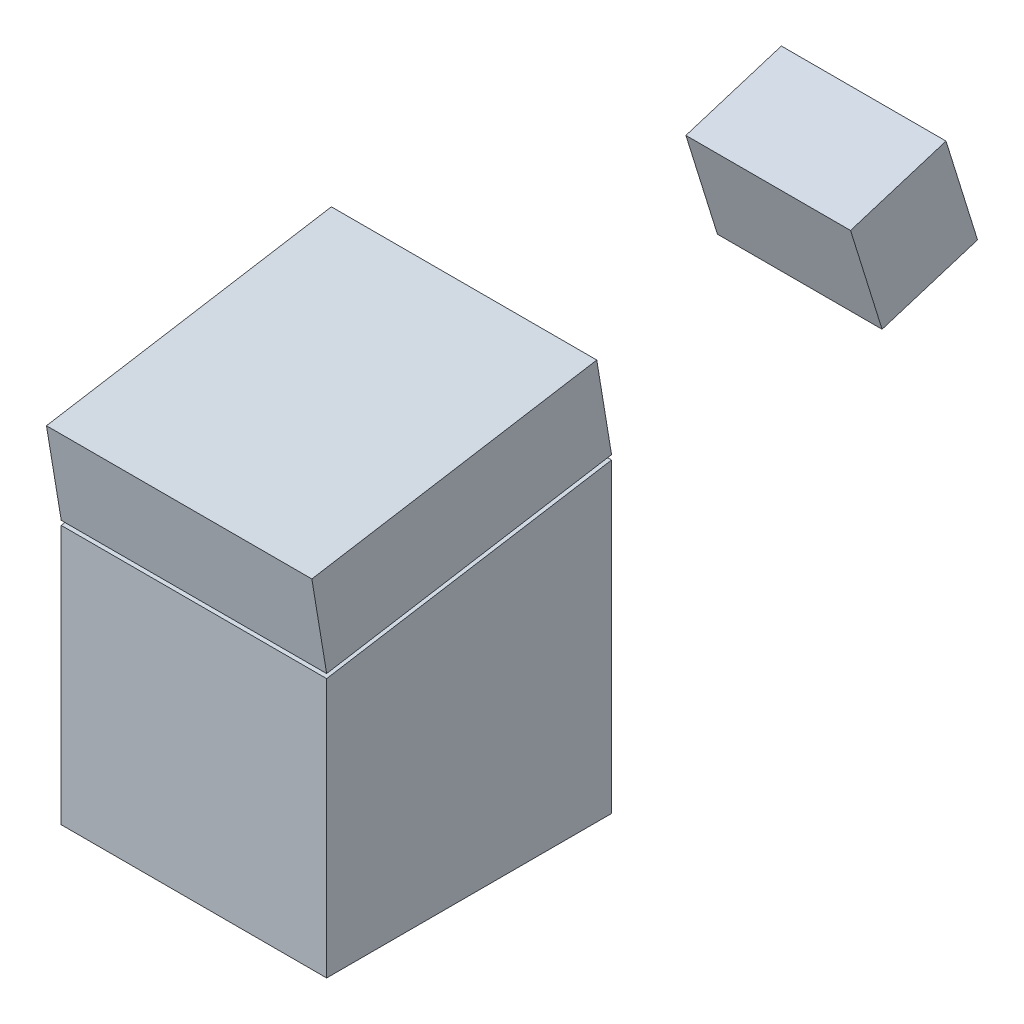
SolidWorks part; units mm, degrees
ref_plane "Front Plane" through (0, 0, 0) normal (0, 0, 1) x (1, 0, 0)
ref_plane "Top Plane" through (0, 0, 0) normal (0, 1, 0) x (1, 0, 0)
ref_plane "Right Plane" through (0, 0, 0) normal (1, 0, 0) x (0, 0, -1)
sketch "Sketch2" plane through (0, 0, 0) normal (1, 0, 0) x (0, 0, -1)
  line L0 (-1035.0443, 461.4168) -> (-1379.1531, 404.8025) construction
  line L1 (-1379.1531, 404.8025) -> (-1379.1531, 91.6547) construction
  line L2 (-1379.1531, 91.6547) -> (-1035.0443, 91.6547) construction
  line L3 (-1035.0443, 91.6547) -> (-1035.0443, 461.4168) construction
  line L4 (-1035.0443, 461.4168) -> (-1379.1531, 404.8025)
  line L5 (-1379.1531, 404.8025) -> (-1379.1531, 91.6547)
  line L6 (-1379.1531, 91.6547) -> (-1035.0443, 91.6547)
  line L7 (-1035.0443, 91.6547) -> (-1035.0443, 461.4168)
extrude "Boss-Extrude1" add sketch "Sketch2" along normal up to vertex (160.2701 mm away) from vertex at -160.2701
sketch "Sketch3" plane through (0, 0, 0) normal (1, 0, 0) x (0, 0, -1)
  line L0 (-1379.1531, 410.0564) -> (-1035.0443, 466.9877) construction
  line L1 (-1397.0086, 517.9805) -> (-1379.1531, 410.0564) construction
  line L2 (-1052.8999, 574.9118) -> (-1397.0086, 517.9805) construction
  line L3 (-1035.0443, 466.9877) -> (-1052.8999, 574.9118) construction
  line L4 (-1379.1531, 410.0564) -> (-1035.0443, 466.9877)
  line L5 (-1397.0086, 517.9805) -> (-1379.1531, 410.0564)
  line L6 (-1052.8999, 574.9118) -> (-1397.0086, 517.9805)
  line L7 (-1035.0443, 466.9877) -> (-1052.8999, 574.9118)
extrude "Boss-Extrude2" add sketch "Sketch3" along normal up to vertex (160.2701 mm away) from vertex at -160.2701 separate body
sketch "Sketch4" plane through (0, 0, 0) normal (1, 0, 0) x (0, 0, -1)
  line L0 (-647.4564, 373.9249) -> (-532.1711, 409.797) construction
  line L1 (-685.5427, 496.3259) -> (-647.4564, 373.9249) construction
  line L2 (-570.2574, 532.198) -> (-685.5427, 496.3259) construction
  line L3 (-532.1711, 409.797) -> (-570.2574, 532.198) construction
  line L4 (-647.4564, 373.9249) -> (-532.1711, 409.797)
  line L5 (-685.5427, 496.3259) -> (-647.4564, 373.9249)
  line L6 (-570.2574, 532.198) -> (-685.5427, 496.3259)
  line L7 (-532.1711, 409.797) -> (-570.2574, 532.198)
extrude "Boss-Extrude3" add sketch "Sketch4" against normal up to vertex (99.4304 mm away) from vertex at 99.4304 separate body
